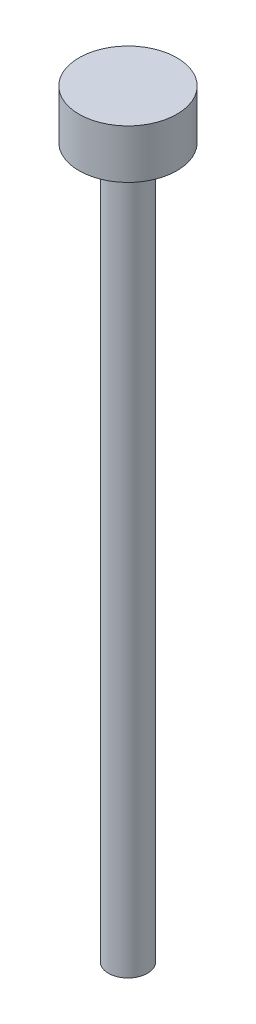
SolidWorks part; units mm, degrees
ref_plane "Front Plane" through (0, 0, 0) normal (0, 0, 1) x (1, 0, 0)
ref_plane "Top Plane" through (0, 0, 0) normal (0, 1, 0) x (1, 0, 0)
ref_plane "Right Plane" through (0, 0, 0) normal (1, 0, 0) x (0, 0, -1)
sketch "Sketch1" plane through (0, 0, 0) normal (0, 1, 0) x (1, 0, 0)
  circle A0 centre (0, 0) radius 2.032
  dimension "D1" = 4.064
extrude "Boss-Extrude1" add sketch "Sketch1" along normal blind 73.66
sketch "Sketch2" plane through (0, 73.66, 0) normal (0, 1, 0) x (1, 0, 0)
  circle A0 centre (0, 0) radius 5.08
  dimension "D1" = 10.16
extrude "Boss-Extrude2" add sketch "Sketch2" along normal blind 5.08
